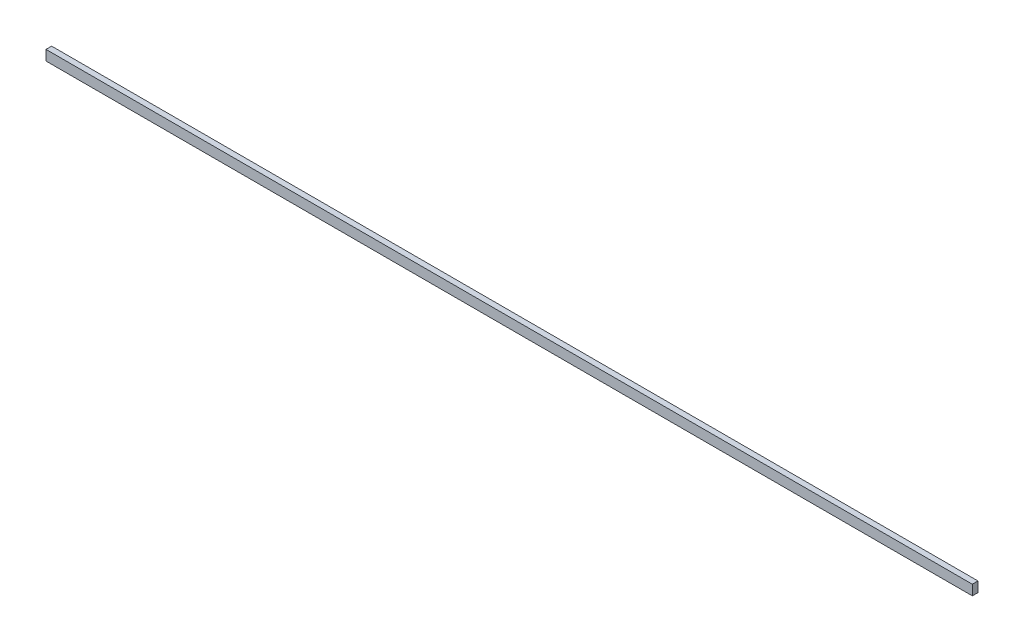
SolidWorks part; units mm, degrees
material "Фанера"
ref_plane "Front Plane" through (0, 0, 0) normal (0, 0, 1) x (1, 0, 0)
ref_plane "Top Plane" through (0, 0, 0) normal (0, 1, 0) x (1, 0, 0)
ref_plane "Right Plane" through (0, 0, 0) normal (1, 0, 0) x (0, 0, -1)
sketch "Эскиз2" plane through (0, 0, 0) normal (0, 0, 1) x (1, 0, 0)
  line L1 (-229.2, -2.5) -> (229.2, -2.5)
  line L2 (-229.2, -2.5) -> (-229.2, 2.5)
  line L3 (-229.2, 2.5) -> (229.2, 2.5)
  line L4 (229.2, -2.5) -> (229.2, 2.5)
  line L5 (-229.2, -2.5) -> (229.2, 2.5) construction
  line L6 (-229.2, 2.5) -> (229.2, -2.5) construction
  point P0 (0, 0)
  point P5 (229.2, 0)
  dimension "D1" = 5
  dimension "D2" = 458.4
extrude "Бобышка-Вытянуть1" add sketch "Эскиз2" along normal mid plane 2.8
equation "\"D2@Эскиз2\"=461.20мм-2.8"
